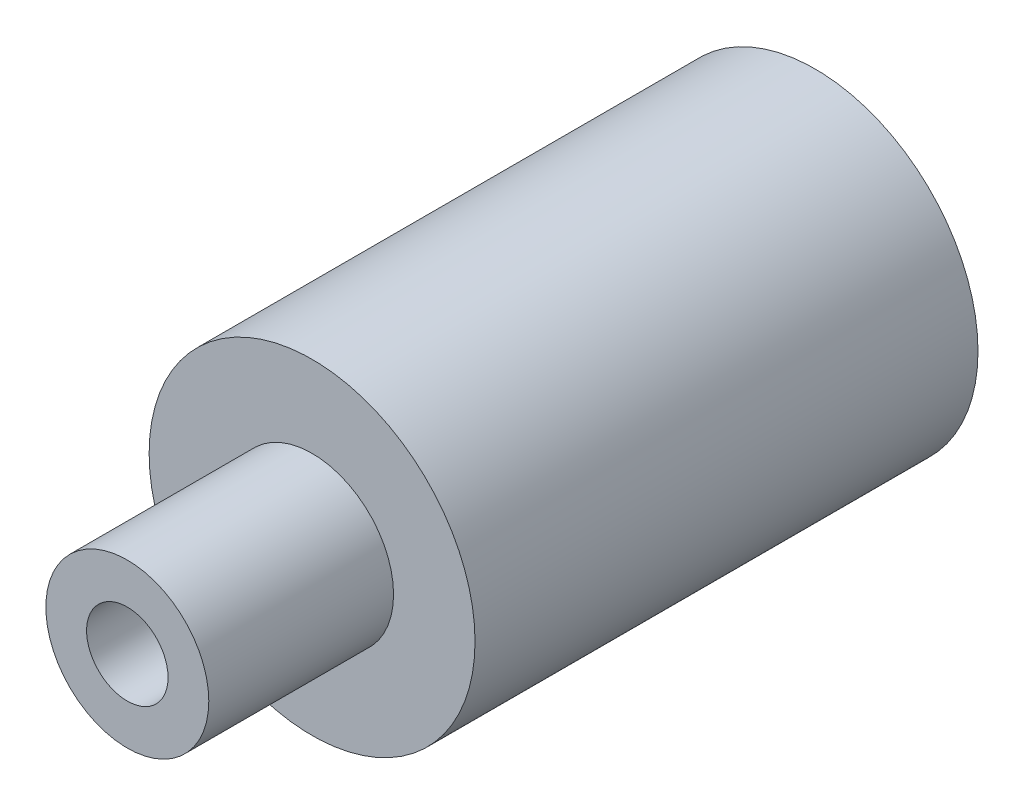
SolidWorks part; units mm, degrees
ref_plane "Front Plane" through (0, 0, 0) normal (0, 0, 1) x (1, 0, 0)
ref_plane "Top Plane" through (0, 0, 0) normal (0, 1, 0) x (1, 0, 0)
ref_plane "Right Plane" through (0, 0, 0) normal (1, 0, 0) x (0, 0, -1)
sketch "Sketch1" plane through (0, 0, 0) normal (1, 0, 0) x (0, 0, -1)
  line L0 (0, 0) -> (73.5169, 0) construction
  line L3 (14.4, 6.35) -> (14.4, 12.7)
  line L4 (0, 0) -> (0, 6.35)
  line L5 (0, 6.35) -> (14.4, 6.35)
  line L6 (14.4, 12.7) -> (53.6, 12.7)
  line L7 (53.6, 12.7) -> (53.6, 0)
  line L8 (53.6, 0) -> (0, 0)
  dimension "D3" = 25.4
  dimension "D6" = 53.6
  dimension "D4" = 12.7
  dimension "D5" = 14.4
revolve "Revolve1" add sketch "Sketch1" angle 360 about L0
sketch "Sketch2" plane through (0, 0, 0) normal (0, 0, 1) x (1, 0, 0)
  circle A0 centre (0, 0) radius 3.175
  dimension "D1" = 6.35
extrude "Cut-Extrude1" cut sketch "Sketch2" against normal blind 25
sketch "Sketch3" plane through (0, 0, -53.6) normal (0, 0, -1) x (-1, 0, 0)
  circle A0 centre (0, 0) radius 6.35
  dimension "D1" = 12.7
extrude "Cut-Extrude2" cut sketch "Sketch3" against normal blind 25
equation "\"D5@Sketch1\"=12.7+1.7"
